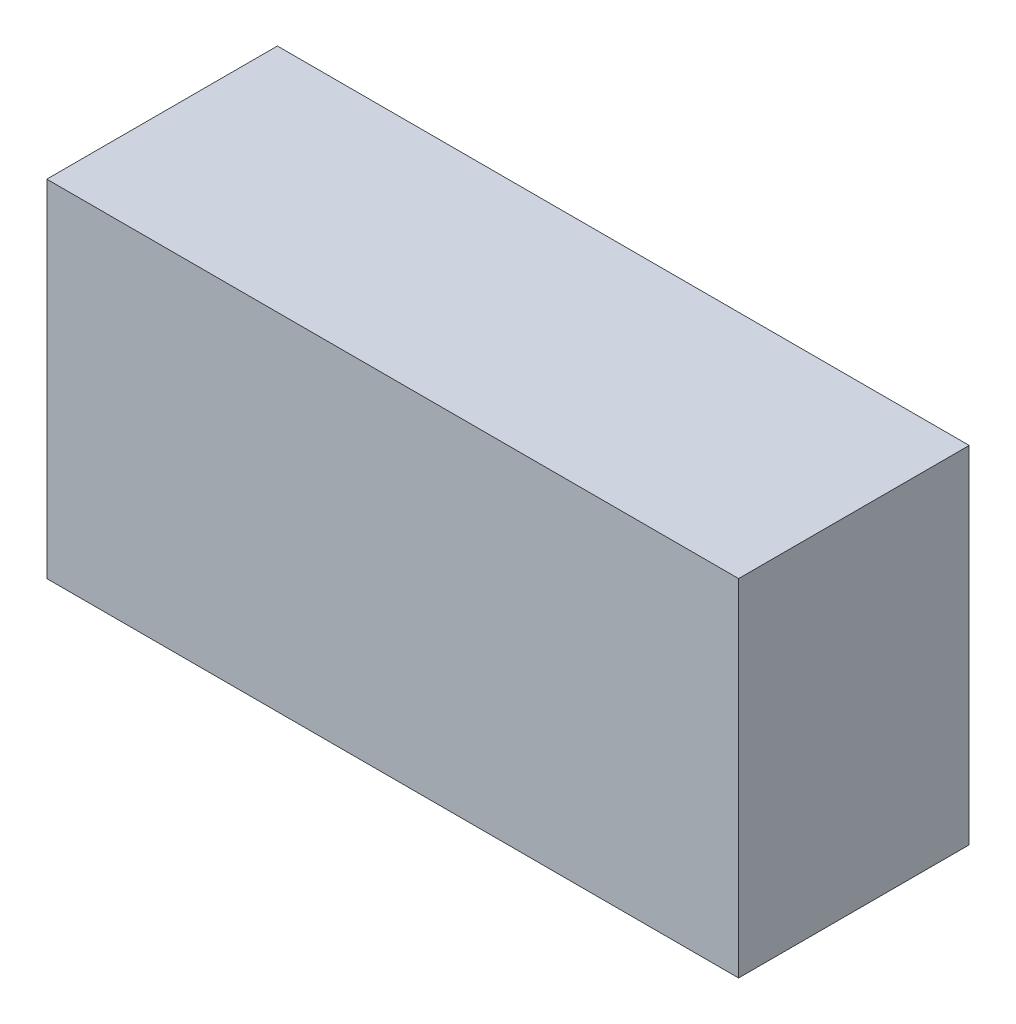
SolidWorks part; units mm, degrees
ref_plane "Front" through (0, 0, 0) normal (0, 0, 1) x (1, 0, 0)
ref_plane "Top" through (0, 0, 0) normal (0, 1, 0) x (1, 0, 0)
ref_plane "Right" through (0, 0, 0) normal (1, 0, 0) x (0, 0, -1)
sketch "Sketch1" plane through (0, 0, 0) normal (0, 0, 1) x (1, 0, 0)
  line L1 (0, 0) -> (152.4, 0)
  line L2 (0, 0) -> (0, 76.2)
  line L3 (0, 76.2) -> (152.4, 76.2)
  line L4 (152.4, 0) -> (152.4, 76.2)
  dimension "D1" = 76.2
  dimension "D2" = 152.4
extrude "Boss-Extrude1" add sketch "Sketch1" along normal blind 50.8
